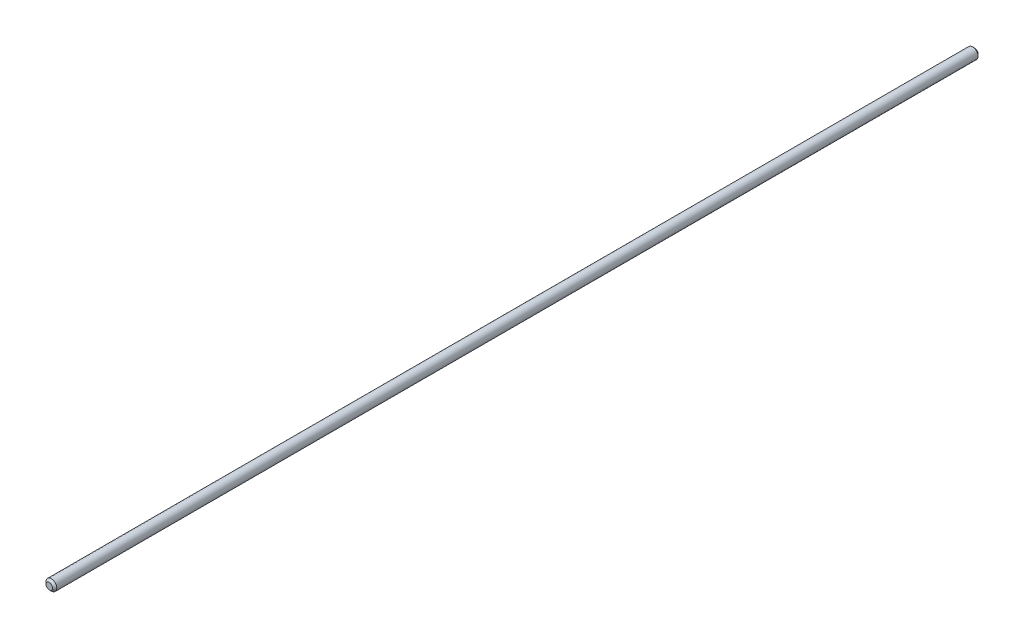
SolidWorks part; units mm, degrees
ref_plane "Front Plane" through (0, 0, 0) normal (0, 0, 1) x (1, 0, 0)
ref_plane "Top Plane" through (0, 0, 0) normal (0, 1, 0) x (1, 0, 0)
ref_plane "Right Plane" through (0, 0, 0) normal (1, 0, 0) x (0, 0, -1)
sketch "Sketch1" plane through (0, 0, 0) normal (0, 0, 1) x (1, 0, 0)
  circle A0 centre (0, 0) radius 2.5
  dimension "D1" = 5
extrude "Boss-Extrude1" add sketch "Sketch1" along normal mid plane 429
chamfer "Chamfer1" distance 1 angle 45 2 edges at (2.5, 0, -214.5) (2.5, 0, 214.5)
